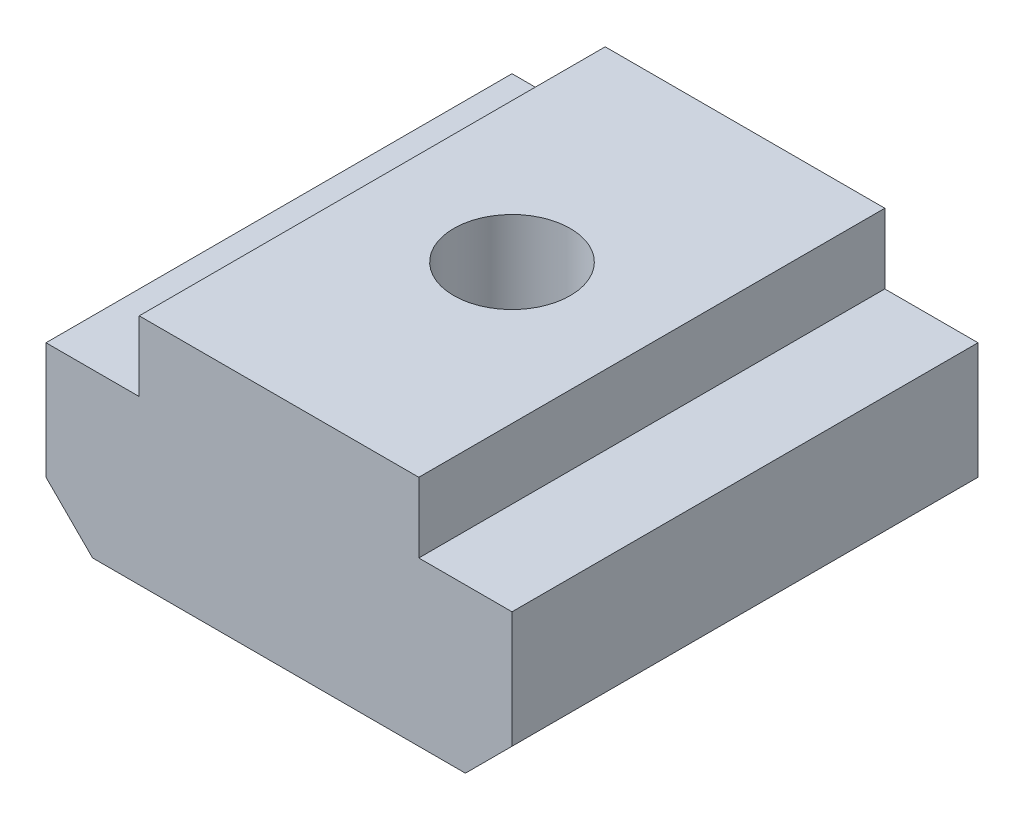
SolidWorks part; units mm, degrees
ref_plane "Front Plane" through (0, 0, 0) normal (0, 0, 1) x (1, 0, 0)
ref_plane "Top Plane" through (0, 0, 0) normal (0, 1, 0) x (1, 0, 0)
ref_plane "Right Plane" through (0, 0, 0) normal (1, 0, 0) x (0, 0, -1)
sketch "Sketch1" plane through (0, 0, 0) normal (0, 0, 1) x (1, 0, 0)
  line L0 (0, 0) -> (0, 46.9655) construction
  line L1 (-4, 0) -> (4, 0)
  line L2 (4, 0) -> (5, 1)
  line L3 (5, 1) -> (5, 3.5)
  line L4 (5, 3.5) -> (3, 3.5)
  line L5 (3, 3.5) -> (3, 5)
  line L6 (3, 5) -> (-3, 5)
  line L7 (-3, 5) -> (-3, 3.5)
  line L8 (-3, 3.5) -> (-5, 3.5)
  line L9 (-5, 3.5) -> (-5, 1)
  line L10 (-5, 1) -> (-4, 0)
  point P10 (0, 5)
  point P14 (-5, 2.25)
  dimension "D1" = 6
  dimension "D2" = 10
  dimension "D3" = 5
  dimension "D4" = 1.5
  dimension "D5" = 5
  dimension "D6" = 1
  dimension "D7" = 1
  dimension "D8" = 1
extrude "Boss-Extrude1" add sketch "Sketch1" along normal blind 10
sketch "Sketch2" plane through (0, 5, 0) normal (0, 1, 0) x (1, 0, 0)
  line L0 (-3, 0) -> (3, -10) construction
  point P4 (0, -5)
hole_wizard "M3x0.5 Tapped Hole1" positions "Sketch3" profile "Sketch4" tap size "M3x0.5" standard "ANSI Metric" end condition through all
sketch "Sketch3" plane through (0, 5, 0) normal (0, 1, 0) x (1, 0, 0)
  point P0 (0, -5)
sketch "Sketch4" plane through (0, 5, 5) normal (1, 0, 0) x (0, 0, 1)
  line L0 (0, 0) -> (0, 5)
  line L1 (0, 5) -> (1.25, 5)
  line L2 (1.25, 5) -> (1.25, 0)
  line L5 (1.25, 0) -> (0, 0)
  line L11 (0, -6.35) -> (0, 107.95) construction
  dimension "Thru Tap Drill Dia." = 2.5
  dimension "Thru Tap Drill Depth" = 5
cosmetic thread "Hole Thread1" parameters "D2"=3
